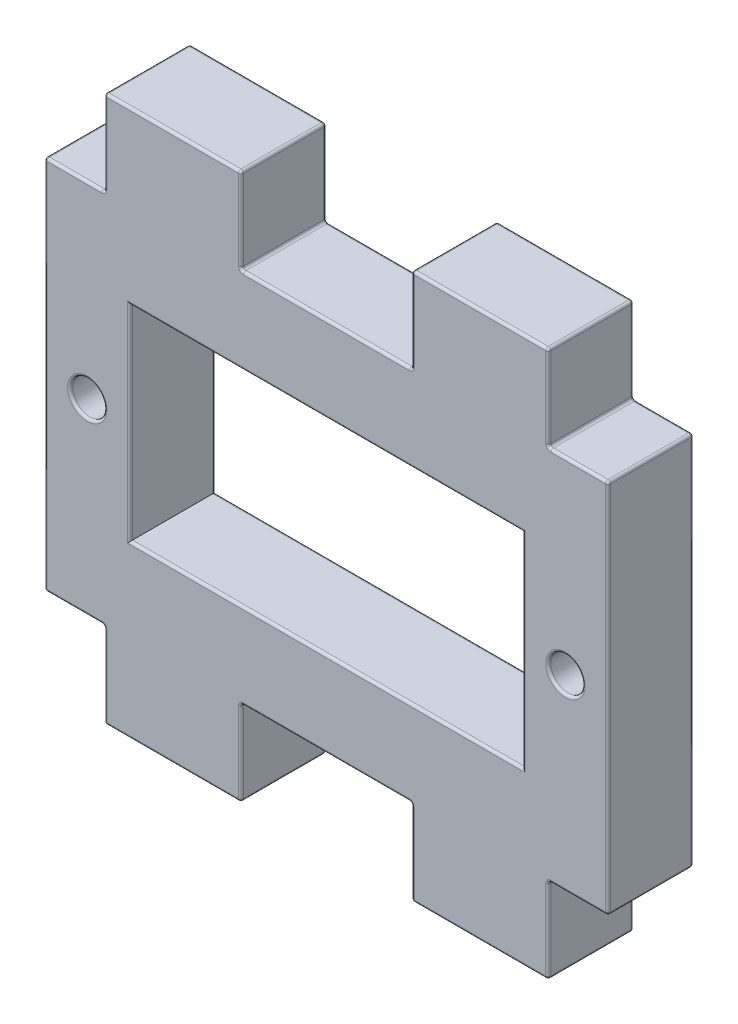
SolidWorks part; units mm, degrees
ref_plane "前视基准面" through (0, 0, 0) normal (0, 0, 1) x (1, 0, 0)
ref_plane "上视基准面" through (0, 0, 0) normal (0, 1, 0) x (1, 0, 0)
ref_plane "右视基准面" through (0, 0, 0) normal (1, 0, 0) x (0, 0, -1)
sketch "草图1" plane through (0, 0, 0) normal (0, 0, 1) x (1, 0, 0)
  line L0 (-16.5, 11) -> (16.5, 11)
  line L1 (-11.5, 6) -> (11.5, 6)
  line L2 (-11.5, 6) -> (-11.5, -6)
  line L3 (-11.5, -6) -> (11.5, -6)
  line L4 (11.5, 6) -> (11.5, -6)
  line L5 (-11.5, 6) -> (11.5, -6) construction
  line L6 (-11.5, -6) -> (11.5, 6) construction
  line L7 (16.5, 11) -> (16.5, -11)
  line L8 (-16.5, -11) -> (16.5, -11)
  line L9 (-16.5, 11) -> (-16.5, -11)
  line L10 (0, 0) -> (0, 31.8563) construction
  line L11 (-13, 16) -> (-5, 16)
  line L12 (-13, 16) -> (-13, 11)
  line L13 (-13, 11) -> (-5, 11)
  line L14 (-5, 16) -> (-5, 11)
  line L15 (0, 0) -> (-32.6375, 0) construction
  line L16 (5, 16) -> (5, 11)
  line L17 (13, 16) -> (5, 16)
  line L18 (13, 16) -> (13, 11)
  line L19 (5, -16) -> (5, -11)
  line L20 (13, -16) -> (13, -11)
  line L21 (-5, -16) -> (-5, -11)
  line L22 (-13, -16) -> (-13, -11)
  line L23 (13, -16) -> (5, -16)
  line L24 (-13, -16) -> (-5, -16)
  circle A0 centre (-14, 0) radius 1
  circle A1 centre (14, 0) radius 1
  point P0 (0, 0)
  dimension "D7" = 2
  dimension "D1" = 12
  dimension "D2" = 23
  dimension "D4" = 3.5
  dimension "D5" = 8
  dimension "D6" = 5
  dimension "D8" = 2.5
  dimension "D3" = 5
extrude "凸台-拉伸1" add sketch "草图1" along normal mid plane 5 contours L0 L9 L8 L7 L1 L4 L3 L2 A0 A1 | L22 L24 L21 L8 | L23 L20 L8 L19 | L18 L17 L16 L0 | L14 L11 L12 L0
fillet "圆角3" radius 0.15 60 edges at (13, 16, 0) (9, 16, -2.5) (13, 13.5, -2.5) (5, 16, 0) (9, 16, 2.5) (13, 13.5, 2.5) (13, 11, 0) (5, 13.5, -2.5) (14.75, 11, -2.5) (5, 11, 0) (5, 13.5, 2.5) (14.75, 11, 2.5) (16.5, 11, 0) (0, 11, -2.5) (16.5, 0, -2.5) (0, 11, 2.5) (-5, 11, 0) (16.5, 0, 2.5) (16.5, -11, 0) (-5, 13.5, -2.5) (14.75, -11, -2.5) (-5, 13.5, 2.5) (-5, 16, 0) (14.75, -11, 2.5) (13, -11, 0) (-9, 16, -2.5) (13, -13.5, -2.5) (-9, 16, 2.5) (-13, 16, 0) (13, -13.5, 2.5) (13, -16, 0) (-13, 13.5, -2.5) (9, -16, -2.5) (-13, 11, 0) (-13, 13.5, 2.5) (9, -16, 2.5) (5, -16, 0) (-14.75, 11, -2.5) (5, -13.5, -2.5) (-14.75, 11, 2.5) (-16.5, 11, 0) (5, -13.5, 2.5) (5, -11, 0) (-16.5, 0, -2.5) (0, -11, -2.5) (-16.5, -11, 0) (-16.5, 0, 2.5) (0, -11, 2.5) (-5, -11, 0) (-14.75, -11, -2.5) (-5, -13.5, -2.5) (-13, -11, 0) (-14.75, -11, 2.5) (-5, -13.5, 2.5) (-5, -16, 0) (-13, -13.5, -2.5) (-9, -16, -2.5) (-13, -13.5, 2.5) (-9, -16, 2.5) (-13, -16, 0)
fillet "圆角4" radius 0.15 12 edges at (11.5, 0, -2.5) (11.5, 0, 2.5) (0, -6, -2.5) (0, -6, 2.5) (-11.5, 0, -2.5) (-11.5, 0, 2.5) (0, 6, -2.5) (0, 6, 2.5) (-13, 0, 2.5) (-13, 0, -2.5) (15, 0, 2.5) (15, 0, -2.5)
